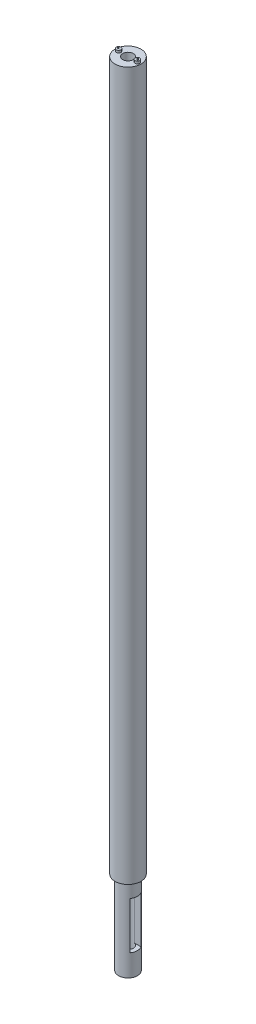
SolidWorks part; units mm, degrees
ref_plane "Front Plane" through (0, 0, 0) normal (0, 0, 1) x (1, 0, 0)
ref_plane "Top Plane" through (0, 0, 0) normal (0, 1, 0) x (1, 0, 0)
ref_plane "Right Plane" through (0, 0, 0) normal (1, 0, 0) x (0, 0, -1)
sketch "Sketch31" plane through (0, 0, 0) normal (0, 0, 1) x (1, 0, 0)
  line L0 (0, 0) -> (0, 35.4702)
sweep "Sweep3" add path "Sketch31" circular profile diameter 8 parameters "D3"=8
sketch "Sketch38" plane through (0, 0, 0) normal (0, 0, 1) x (1, 0, 0)
  line L1 (4, 35.4702) -> (-4, 35.4702) construction
  line L2 (0, 35.4702) -> (0, 336.2875)
sweep "Sweep4" add path "Sketch38" circular profile diameter 11 parameters "D3"=11
sketch "Sketch45" plane through (0, 0, 0) normal (0, 1, 0) x (1, 0, 0)
  circle A0 centre (0, 0) radius 2.25
extrude "Cut-Extrude2" cut sketch "Sketch45" along normal through all
sketch3d "3DSketch1"
  line L1 (0, 336.2875, 0) -> (0, 0, 0) construction
  line L2 (0, 336.2875, 0) -> (2.25, 336.2875, 0)
  line L18 (-5.5, 336.2875, 0) -> (-5.5, 336.2875, -5.5)
  line L19 (-5.5, 336.2875, -5.5) -> (0, 336.2875, -5.5)
  line L20 (0, 336.2875, -5.5) -> (5.5, 336.2875, -5.5)
  line L21 (5.5, 336.2875, -5.5) -> (5.5, 336.2875, 0)
  line L22 (0, 336.2875, 5.5) -> (5.5, 336.2875, 5.5)
  line L23 (5.5, 336.2875, 5.5) -> (5.5, 336.2875, 0)
  line L24 (0, 336.2875, 5.5) -> (-5.5, 336.2875, 5.5)
  line L25 (-5.5, 336.2875, 5.5) -> (-5.5, 336.2875, 0)
  circle A0 centre (0, 336.2875, 0) radius 2.25
  circle A1 centre (0, 336.2875, 0) radius 5.5 construction
  point P3 (0, 338.5375, 0)
  point P6 (0, 341.7875, 0)
  dimension "D1" = 5.5
  dimension "D3" = 5.5
  dimension "D2" = 5.5
  dimension "D4" = 5.5
  dimension "D5" = 5.5
  dimension "D6" = 5.5
  dimension "D7" = 5.5
  dimension "D8" = 5.5
sketch3d "3DSketch4"
  line L0 (4.125, 336.2875, 0) -> (4.125, 337.7875, 0)
  line L1 (-4.125, 336.2875, 0) -> (-4.125, 337.7875, 0)
  point P5 (-4.125, 336.2875, 0)
  point P6 (4.125, 336.2875, 0)
  dimension "D1" = 1.5
  dimension "D2" = 1.5
sweep "Sweep5" add path "3DSketch4" circular profile diameter 0.5 parameters "D3"=0.5
sketch3d "3DSketch5"
  line L0 (-4.125, 336.2875, 0) -> (-4.125, 337.7875, 0)
  line L1 (-5.5, 336.2875, 0) -> (-2.75, 336.2875, 0)
  line L2 (-4.125, 336.2875, 0) -> (-2.75, 336.2875, 0)
  dimension "D1" = 1.5
  dimension "D2" = 4.125
sweep "Sweep6" add path "3DSketch5" circular profile diameter 0.5 parameters "D3"=0.5
sketch "Sketch72" plane through (0, 0, 0) normal (1, 0, 0) x (0, 0, -1)
  line L0 (-2.318, 9.2361) -> (2.182, 9.2361)
  line L2 (-2.318, 9.2361) -> (-2.318, 29.2361)
  line L3 (-2.318, 29.2361) -> (2.182, 29.2361)
  line L4 (2.182, 29.2361) -> (2.182, 9.2361)
  dimension "D1" = 20
  dimension "D2" = 4.5
extrude "Cut-Extrude6" cut sketch "Sketch72" along normal blind 20
sketch "Sketch73" plane through (0, 0, 0) normal (0, 0, 1) x (1, 0, 0)
  line L0 (3.875, 337.7212) -> (4.3306, 337.589)
  line L1 (3.875, 337.7875) -> (3.875, 336.2875) construction
sketch "Sketch77" plane through (0, 336.2875, 0) normal (0, 1, 0) x (1, 0, 0)
  circle A0 centre (-4, 0) radius 1
  circle A1 centre (4, 0) radius 1
  point P2 (-0.8445, 10.0637)
  point P7 (-12.7172, 15.9712)
  dimension "D1" = 2
  dimension "D2" = 4
  dimension "D3" = 4
sketch "Sketch78" plane through (0, 0, 0) normal (0, 0, 1) x (1, 0, 0)
  line L0 (-4, 336.2875) -> (-4, 337.7875)
  line L1 (4, 336.2875) -> (4, 337.7875)
  dimension "D1" = 1.5
extrude "Boss-Extrude1" add sketch "Sketch77" along normal blind 1
